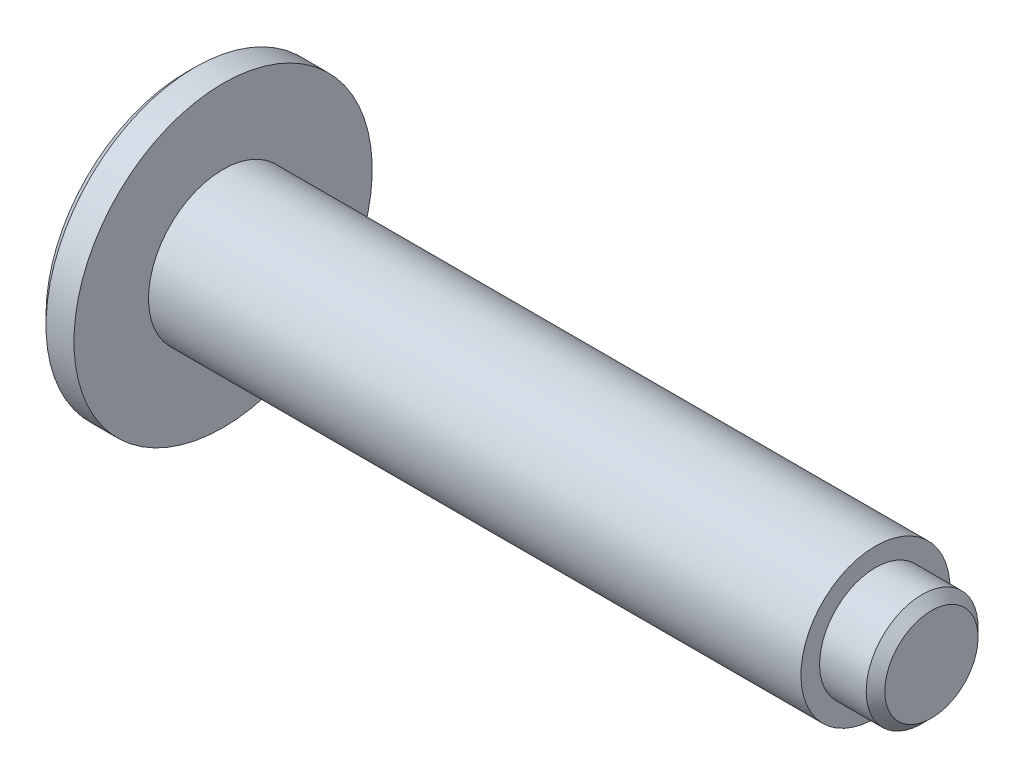
SolidWorks part; units mm, degrees
ref_plane "Front" through (0, 0, 0) normal (0, 0, 1) x (1, 0, 0)
ref_plane "Top" through (0, 0, 0) normal (0, 1, 0) x (1, 0, 0)
ref_plane "Right" through (0, 0, 0) normal (1, 0, 0) x (0, 0, -1)
sketch "草图1" plane through (0, 0, 0) normal (0, 0, 1) x (1, 0, 0)
  line L0 (-12.3014, 0.3346) -> (-12.3014, 8.3346)
  line L1 (-12.3014, 8.3346) -> (-10.3014, 8.3346)
  line L2 (-10.3014, 8.3346) -> (-10.3014, 4.3346)
  line L3 (-10.3014, 4.3346) -> (24.6986, 4.3346)
  line L4 (24.6986, 4.3346) -> (24.6986, 3.3346)
  line L5 (24.6986, 3.3346) -> (27.6986, 3.3346)
  line L6 (27.6986, 3.3346) -> (27.6986, 0.3346)
  line L7 (27.6986, 0.3346) -> (-12.3014, 0.3346)
  dimension "D1" = 8
  dimension "D2" = 2
  dimension "D3" = 35
  dimension "D4" = 3
  dimension "D5" = 3
  dimension "D6" = 4
revolve "旋转1" add sketch "草图1" angle 360 about L7
chamfer "倒角1" distance 0.5 angle 45 2 edges at (-12.3014, 8.3346, 0) (27.6986, 3.3346, 0)
